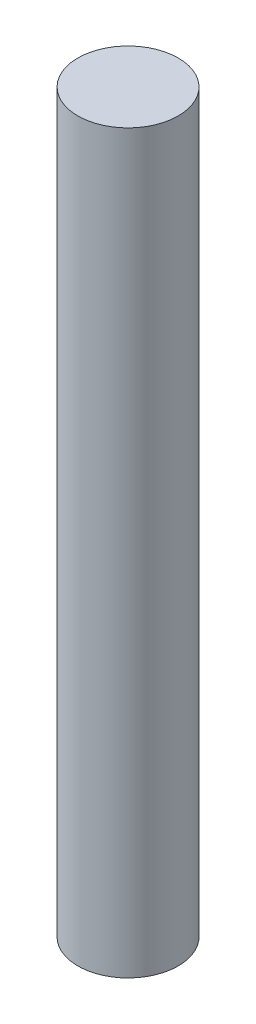
SolidWorks part; units mm, degrees
ref_plane "Alzado" through (0, 0, 0) normal (0, 0, 1) x (1, 0, 0)
ref_plane "Planta" through (0, 0, 0) normal (0, 1, 0) x (1, 0, 0)
ref_plane "Vista lateral" through (0, 0, 0) normal (1, 0, 0) x (0, 0, -1)
sketch "Croquis_perfil" plane through (0, 0, 0) normal (0, 0, 1) x (1, 0, 0)
  line L0 (0, 0) -> (0, 220) construction
  line L1 (0, 0) -> (15, 0)
  line L2 (15, 0) -> (15, 220)
  line L3 (15, 220) -> (0, 220)
  line L4 (0, 220) -> (0, 0)
  dimension "D1" = 15
  dimension "D2" = 220
revolve "Poste_D30x220" add sketch "Croquis_perfil" angle 360 about L0
sketch "Croquis_agujeros_montaje" plane through (0, 0, 0) normal (0, 1, 0) x (1, 0, 0)
  circle A0 centre (0, 0) radius 4
  dimension "D1" = 8
extrude "Agujero_inserto_M6" cut sketch "Croquis_agujeros_montaje" along normal blind 14
